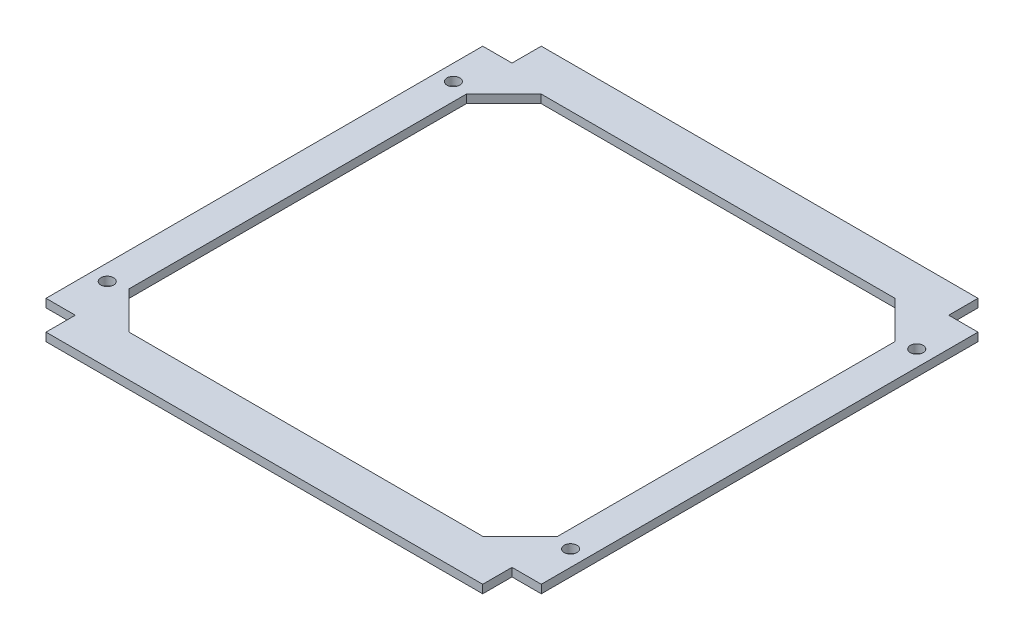
SolidWorks part; units mm, degrees
ref_plane "Front Plane" through (0, 0, 0) normal (0, 0, 1) x (1, 0, 0)
ref_plane "Top Plane" through (0, 0, 0) normal (0, 1, 0) x (1, 0, 0)
ref_plane "Right Plane" through (0, 0, 0) normal (1, 0, 0) x (0, 0, -1)
sketch "Sketch1" plane through (0, 0, 0) normal (0, 1, 0) x (1, 0, 0)
  line L0 (-41, -41) -> (-46.5, -41)
  line L1 (41, -46.5) -> (-41, -46.5)
  line L2 (46.5, -41) -> (46.5, 41)
  line L3 (41, 46.5) -> (-41, 46.5)
  line L5 (-46.5, -41) -> (-46.5, 41)
  line L6 (46.5, -46.5) -> (-46.5, 46.5) construction
  line L7 (46.5, 46.5) -> (-46.5, -46.5) construction
  line L8 (41, -41) -> (-41, -41) construction
  line L9 (41, -41) -> (41, 41) construction
  line L10 (41, 41) -> (-41, 41) construction
  line L11 (-41, -41) -> (-41, 41) construction
  line L12 (41, -41) -> (-41, 41) construction
  line L13 (41, 41) -> (-41, -41) construction
  line L14 (-41, -41) -> (-41, -46.5)
  line L15 (-41, 41) -> (-46.5, 41)
  line L16 (-41, 41) -> (-41, 46.5)
  line L17 (41, 41) -> (41, 46.5)
  line L18 (41, 41) -> (46.5, 41)
  line L19 (41, -41) -> (46.5, -41)
  line L20 (41, -41) -> (41, -46.5)
  point P0 (0, 0)
  point P2 (-49.3567, -47.5952)
  point P4 (49.2433, -47.5952)
  point P5 (-49.3567, 41.6048)
  point P6 (-43.2567, 47.7048)
  point P10 (46.4433, 44.4048)
  point P11 (43.1433, 47.7048)
  point P12 (-46.8567, -45.0952)
  point P13 (-46.8567, 41.6048)
  point P14 (46.7433, -45.0952)
  point P15 (46.7433, 41.6048)
  point P16 (0, 0)
  point P35 (0, 0)
  point P42 (-43.2567, 44.0048)
  point P43 (43.1433, 44.0048)
  dimension "D1" = 93
  dimension "D2" = 93
  dimension "D3" = 82
  dimension "D4" = 5.5
  dimension "D6" = 4
  dimension "D7" = 82
extrude "Boss-Extrude1" add sketch "Sketch1" along normal blind 1.56
sketch "Sketch2" plane through (0, 1.56, 0) normal (0, 1, 0) x (1, 0, 0)
  line L0 (-40.2433, 31.7048) -> (-33.2433, 38.7048)
  line L1 (33.2433, -38.7048) -> (-33.2433, -38.7048)
  line L2 (40.2433, -31.7048) -> (40.2433, 31.7048)
  line L3 (33.2433, 38.7048) -> (-33.2433, 38.7048)
  line L4 (-40.2433, -31.7048) -> (-40.2433, 31.7048)
  line L5 (40.2433, -38.7048) -> (-40.2433, 38.7048) construction
  line L6 (40.2433, 38.7048) -> (-40.2433, -38.7048) construction
  line L7 (40.2433, 31.7048) -> (33.2433, 38.7048)
  line L10 (33.2433, -38.7048) -> (40.2433, -31.7048)
  line L11 (-33.2433, -38.7048) -> (-40.2433, -31.7048)
  line L12 (41, 46.5) -> (-41, 46.5) construction
  line L13 (46.5, -41) -> (46.5, 41) construction
  point P0 (0, 0)
  point P24 (-40.2433, 38.7048)
  point P27 (40.2433, 38.7048)
  point P30 (40.2433, -38.7048)
  point P33 (-40.2433, -38.7048)
  dimension "D1" = 7.7952
  dimension "D2" = 6.2567
extrude "Cut-Extrude1" cut sketch "Sketch2" against normal blind 1.56
sketch "Sketch3" plane through (0, 0, 0) normal (0, 1, 0) x (1, 0, 0)
  circle A0 centre (0, 0) radius 38.5
sketch "Sketch4" plane through (0, 1.56, 0) normal (0, 1, 0) x (1, 0, 0)
  line L1 (43.5, -32.5) -> (-43.5, -32.5) construction
  line L2 (43.5, -32.5) -> (43.5, 32.5) construction
  line L3 (43.5, 32.5) -> (-43.5, 32.5) construction
  line L4 (-43.5, -32.5) -> (-43.5, 32.5) construction
  line L5 (43.5, -32.5) -> (-43.5, 32.5) construction
  line L6 (43.5, 32.5) -> (-43.5, -32.5) construction
  point P0 (0, 0)
  dimension "D1" = 65
  dimension "D2" = 87
hole_wizard "M2 Clearance Hole1" positions "Sketch6" profile "Sketch5" hole size "M2" standard "ANSI Metric"
sketch "Sketch6" plane through (0, 1.56, 0) normal (0, 1, 0) x (1, 0, 0)
  point P0 (-43.5, -32.5)
  point P3 (-43.5, 32.5)
  point P6 (43.5, 32.5)
  point P9 (43.5, -32.5)
sketch "Sketch5" plane through (-43.5, 1.56, 32.5) normal (1, 0, 0) x (0, 0, 1)
  line L0 (0, 0) -> (0, 38.821)
  line L1 (0, 38.821) -> (1.2, 38.1)
  line L2 (1.2, 38.1) -> (1.2, 0)
  line L5 (1.2, 0) -> (0, 0)
  line L10 (0, 38.821) -> (-1.2, 38.1) construction
  line L11 (0, -6.35) -> (0, 107.95) construction
  dimension "Hole Dia." = 2.4
  dimension "Hole Depth" = 38.1
  dimension "Drill Angle" = 118
